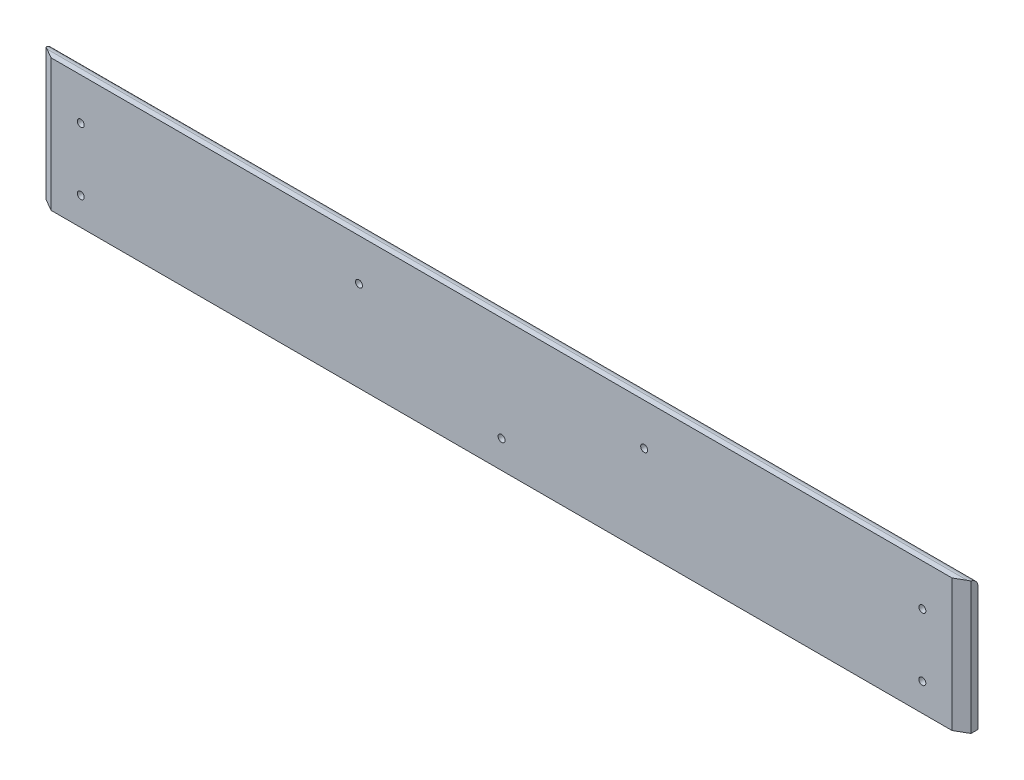
SolidWorks part; units mm, degrees
material "Настроенная пользователем пластмасса"
ref_plane "Спереди" through (0, 0, 0) normal (0, 0, 1) x (1, 0, 0)
ref_plane "Сверху" through (0, 0, 0) normal (0, 1, 0) x (1, 0, 0)
ref_plane "Справа" through (0, 0, 0) normal (1, 0, 0) x (0, 0, -1)
sketch "Эскиз1" plane through (0, 0, 0) normal (0, 0, 1) x (1, 0, 0)
  line L1 (-332.5, -47.5) -> (332.5, -47.5)
  line L2 (-332.5, -47.5) -> (-332.5, 47.5)
  line L3 (-332.5, 47.5) -> (332.5, 47.5)
  line L4 (332.5, -47.5) -> (332.5, 47.5)
  line L5 (0, 47.5) -> (0, -47.5) construction
  line L6 (-332.5, 0) -> (332.5, 0) construction
  point P0 (0, 0)
  dimension "D1" = 665
  dimension "D2" = 95
extrude "Бобышка-Вытянуть1" add sketch "Эскиз1" along normal mid plane 10
fillet "Скругление1" radius 6 1 edges at (0, 47.5, -5)
chamfer "Фаска1" distance 5 angle 60 2 edges at (332.5, 0, 5) (-332.5, 0, 5)
sketch "Эскиз3" plane through (0, 0, 5) normal (0, 0, 1) x (1, 0, 0)
  line L0 (-323.8397, -47.5) -> (323.8397, -47.5) construction
  line L1 (-332.5, -47.5) -> (-332.5, 47.4161) construction
  line L2 (332.5, 47.4161) -> (332.5, -47.5) construction
  line L3 (0, -50) -> (0, 50) construction
  circle A0 centre (-302.5, -27.5) radius 2.5
  circle A1 centre (0, -27.5) radius 2.5
  circle A2 centre (302.5, -27.5) radius 2.5
  circle A3 centre (-302.5, 17.5) radius 2.5
  circle A4 centre (302.5, 17.5) radius 2.5
  circle A5 centre (-102.5, 17.5) radius 2.5
  circle A6 centre (102.5, 17.5) radius 2.5
  dimension "D1" = 5
  dimension "D2" = 20
  dimension "D3" = 30
  dimension "D4" = 30
  dimension "D5" = 45
  dimension "D6" = 200
  dimension "D7" = 200
extrude "Вырез-Вытянуть1" cut sketch "Эскиз3" against normal through all
chamfer "Фаска2" distance 2 angle 45 7 edges at (-300, -27.5, -5) (-300, 17.5, -5) (-100, 17.5, -5) (2.5, -27.5, -5) (105, 17.5, -5) (305, -27.5, -5) (305, 17.5, -5)
